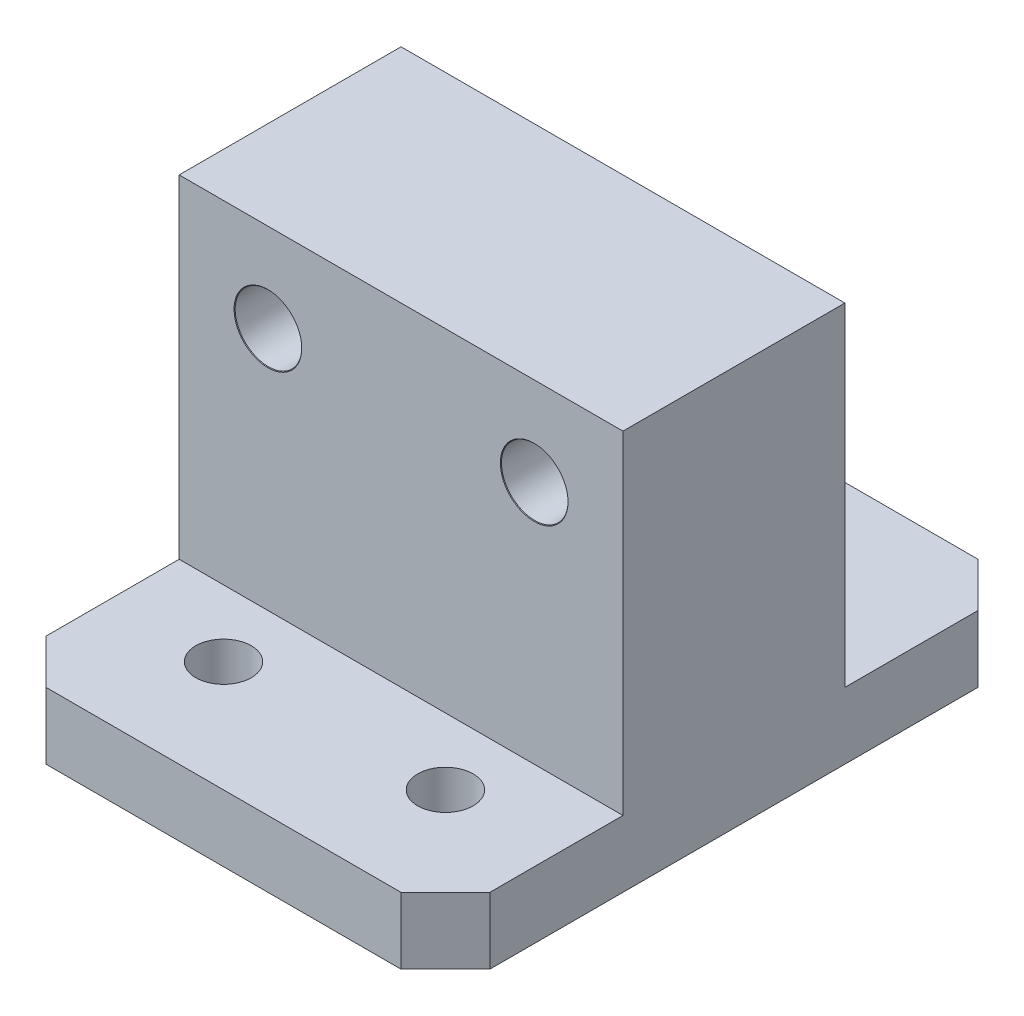
SolidWorks part; units mm, degrees
ref_plane "前视基准面" through (0, 0, 0) normal (0, 0, 1) x (1, 0, 0)
ref_plane "上视基准面" through (0, 0, 0) normal (0, 1, 0) x (1, 0, 0)
ref_plane "右视基准面" through (0, 0, 0) normal (1, 0, 0) x (0, 0, -1)
other "Configuration Table"
sketch "草图1" plane through (0, 0, 0) normal (0, 0, 1) x (1, 0, 0)
  line L1 (0, 0) -> (20, 0)
  line L2 (0, 0) -> (0, 15)
  line L3 (0, 15) -> (20, 15)
  line L4 (20, 0) -> (20, 15)
  dimension "D1" = 20
  dimension "D2" = 15
extrude "凸台-拉伸1" add sketch "草图1" along normal blind 10
hole_wizard "Ø3.0mm 暗销孔1" positions "3D草图1" profile "草图2" hole size "Ø3.0" standard "GB" end condition through all
sketch3d "3D草图1"
  line L0 (20, 15, 10) -> (0, 15, 10) construction
  point P0 (4, 11, 10)
  point P2 (16, 11, 10)
  dimension "D1" = 12
  dimension "D2" = 4
  dimension "D3" = 4
  dimension "D4" = 4
sketch "草图2" plane through (4, 11, 10) normal (1, 0, 0) x (0, -1, 0)
  line L0 (0, 0) -> (0, 10)
  line L1 (0, 10) -> (1.5, 10)
  line L2 (1.5, 10) -> (1.5, 0.025)
  line L3 (1.5, 0.025) -> (1.525, 0)
  line L5 (1.525, 0) -> (0, 0)
  line L6 (-1.5, 0.025) -> (-1.525, 0) construction
  line L11 (0, -6.35) -> (0, 107.95) construction
  dimension "通孔孔直径" = 3
  dimension "通孔孔深度" = 10
  dimension "近端锥形沉头孔直径" = 3.05
  dimension "近端锥形沉头孔角度" = 90
sketch "草图3" plane through (0, 0, 0) normal (0, -1, 0) x (1, 0, 0)
  line L0 (20, 10) -> (20, 0) construction
  line L1 (20, 18) -> (0, 18)
  line L2 (20, 18) -> (20, -8)
  line L3 (20, -8) -> (0, -8)
  line L4 (0, 18) -> (0, -8)
  line L5 (0, 10) -> (0, 0) construction
  line L6 (0, 10) -> (20, 10) construction
  line L7 (0, 0) -> (20, 0) construction
  dimension "D1" = 8
  dimension "D2" = 8
extrude "凸台-拉伸2" add sketch "草图3" along normal blind 3
sketch "草图4" plane through (0, -3, 0) normal (0, -1, 0) x (1, 0, 0)
  line L0 (0, 18) -> (0, -8) construction
  line L1 (5, 13) -> (15, 13)
  line L2 (5, 13) -> (5, -3)
  line L3 (5, -3) -> (15, -3)
  line L4 (15, 13) -> (15, -3)
  line L5 (20, 18) -> (0, 18) construction
  dimension "D1" = 16
  dimension "D2" = 10
  dimension "D3" = 5
  dimension "D4" = 5
hole_wizard "Ø2.5mm 暗销孔1" positions "3D草图2" profile "草图5" hole size "Ø2.5" standard "GB" end condition up to next
sketch3d "3D草图2"
  point P0 (5, -3, 13)
  point P3 (15, -3, 13)
  point P6 (5, -3, -3)
  point P9 (15, -3, -3)
sketch "草图5" plane through (5, -3, 13) normal (1, 0, 0) x (0, 0, -1)
  line L0 (0, 0) -> (0, 3)
  line L1 (0, 3) -> (1.25, 3)
  line L2 (1.25, 3) -> (1.25, 0.025)
  line L3 (1.25, 0.025) -> (1.275, 0)
  line L5 (1.275, 0) -> (0, 0)
  line L6 (-1.25, 0.025) -> (-1.275, 0) construction
  line L11 (0, -6.35) -> (0, 107.95) construction
  dimension "通孔孔直径" = 2.5
  dimension "通孔孔深度" = 3
  dimension "近端锥形沉头孔直径" = 2.55
  dimension "近端锥形沉头孔角度" = 90
chamfer "倒角1" distance 2 angle 45 4 edges at (20, -1.5, -8) (20, -1.5, 18) (0, -1.5, 18) (0, -1.5, -8)
